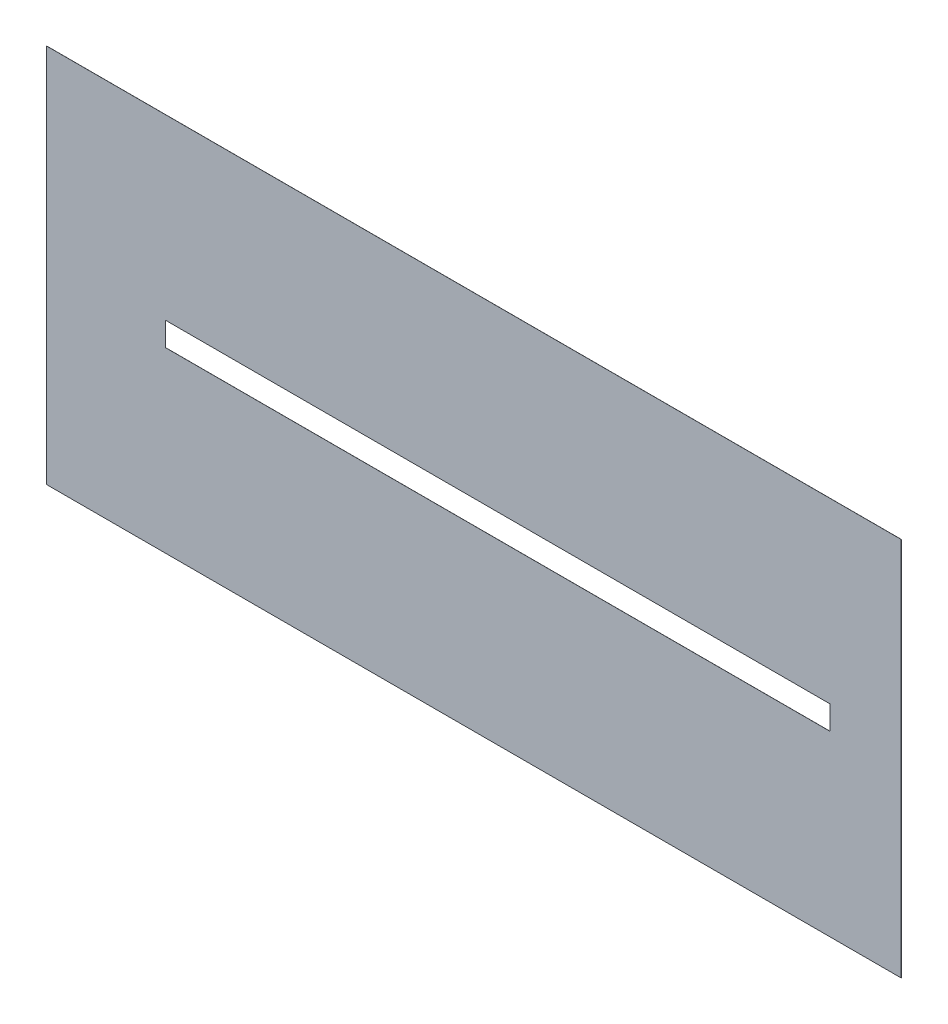
SolidWorks part; units mm, degrees
ref_plane "Front Plane" through (0, 0, 0) normal (0, 0, 1) x (1, 0, 0)
ref_plane "Top Plane" through (0, 0, 0) normal (0, 1, 0) x (1, 0, 0)
ref_plane "Right Plane" through (0, 0, 0) normal (1, 0, 0) x (0, 0, -1)
sketch "Sketch2" plane through (0, 0, 0) normal (0, 0, 1) x (1, 0, 0)
  line L0 (-1987.3494, 0) -> (1987.3494, 0) construction
  line L1 (0, 1542.0431) -> (0, -1542.0431) construction
  line L3 (-1000, 2000) -> (8000, 2000)
  line L4 (-1000, 2000) -> (-1000, -2000)
  line L5 (-1000, -2000) -> (8000, -2000)
  line L6 (8000, 2000) -> (8000, -2000)
  line L7 (250, 125) -> (7250, 125)
  line L8 (250, 125) -> (250, -125)
  line L9 (250, -125) -> (7250, -125)
  line L10 (7250, 125) -> (7250, -125)
  dimension "D1" = 9000
  dimension "D2" = 4000
  dimension "D3" = 2000
  dimension "D4" = 1000
  dimension "D5" = 250
  dimension "D6" = 125
  dimension "D7" = 250
  dimension "D8" = 7000
extrude "Boss-Extrude3" add sketch "Sketch2" against normal blind 1
